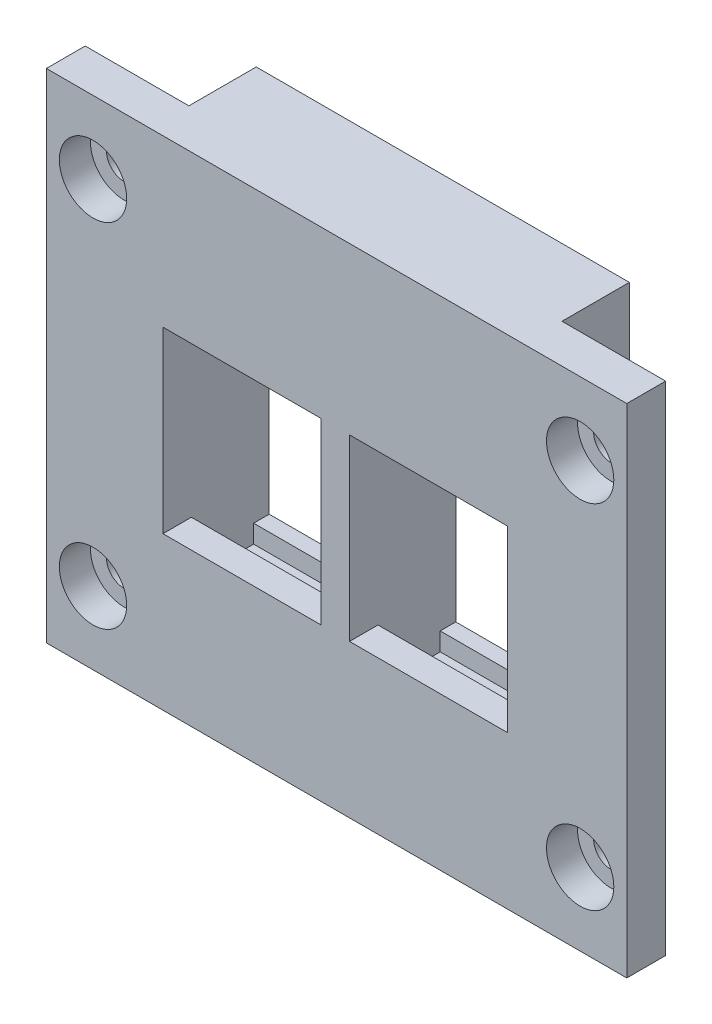
SolidWorks part; units mm, degrees
ref_plane "Front Plane" through (0, 0, 0) normal (0, 0, 1) x (1, 0, 0)
ref_plane "Top Plane" through (0, 0, 0) normal (0, 1, 0) x (1, 0, 0)
ref_plane "Right Plane" through (0, 0, 0) normal (1, 0, 0) x (0, 0, -1)
sketch "Sketch1" plane through (0, 0, 0) normal (0, 0, 1) x (1, 0, 0)
  line L1 (-18, 24) -> (18, 24)
  line L2 (-18, 24) -> (-18, -24)
  line L3 (-18, -24) -> (18, -24)
  line L4 (18, 24) -> (18, -24)
  line L5 (-18, 24) -> (18, -24) construction
  line L6 (-18, -24) -> (18, 24) construction
  point P0 (0, 0)
  dimension "D1" = 36
  dimension "D2" = 48
extrude "Boss-Extrude1" add sketch "Sketch1" along normal blind 6.5 and the other way blind 3.75
sketch "Sketch2" plane through (0, 0, 6.5) normal (0, 0, -1) x (-1, 0, 0)
  line L0 (18, -24) -> (-18, -24) construction
  line L1 (-28, -24) -> (28, -24)
  line L2 (-28, -24) -> (-28, 24)
  line L3 (-28, 24) -> (28, 24)
  line L4 (28, -24) -> (28, 24)
  line L5 (-18, 24) -> (18, 24) construction
  point P6 (0, 24)
  dimension "D1" = 56
extrude "Boss-Extrude2" add sketch "Sketch2" along normal blind 3.75
sketch "Sketch6" plane through (0, 0, 6.5) normal (0, 0, 1) x (1, 0, 0)
  line L0 (-28, -24) -> (-28, 24) construction
  line L1 (28, -24) -> (-28, -24) construction
  line L2 (-28, 24) -> (28, 24) construction
  line L3 (28, 24) -> (28, -24) construction
  point P0 (-23.5, 17)
  point P2 (-23.5, -17)
  point P4 (23.5, 17)
  point P6 (23.5, -17)
  dimension "D1" = 4.5
  dimension "D2" = 7
  dimension "D3" = 7
  dimension "D4" = 4.5
hole_wizard "CBORE for M3 SHCS1" positions "Sketch6" profile "Sketch5" counterbore size "M3" standard "ANSI Metric"
sketch "Sketch5" plane through (-23.5, 17, 6.5) normal (1, 0, 0) x (0, -1, 0)
  line L0 (0, 0) -> (0, 11.1215)
  line L1 (0, 11.1215) -> (1.7, 10.1)
  line L2 (1.7, 10.1) -> (1.7, 3)
  line L3 (1.7, 3) -> (3.25, 3)
  line L4 (3.25, 3) -> (3.25, 0)
  line L5 (3.25, 0) -> (0, 0)
  line L10 (0, 11.1215) -> (-1.7, 10.1) construction
  line L11 (0, -6.35) -> (0, 107.95) construction
  dimension "Hole Dia." = 3.4
  dimension "Hole Depth" = 10.1
  dimension "C'Bore Dia." = 6.5
  dimension "C'Bore Depth" = 3
  dimension "Drill Angle" = 118
ref_plane "Plane1" through (16.5, 0, 0) normal (1, 0, 0) x (0, 0, -1)
sketch "Sketch7" plane through (16.5, 0, 0) normal (1, 0, 0) x (0, 0, -1)
  line L0 (-5.7534, 23.5034) -> (-5.7534, 7.5034) construction
  line L1 (-5.7534, 7.5034) -> (0.7466, 7.5034) construction
  line L2 (2.2466, 7.5034) -> (2.2466, 9.0034) construction
  line L3 (4.2466, -12.9966) -> (8.1247, -12.9966) construction
  line L4 (2.2466, 9.0034) -> (0.7466, 7.5034) construction
  line L5 (2.2466, 7.5034) -> (3.7466, 7.5034) construction
  line L6 (4.2466, 7.5034) -> (4.2466, 23.5034) construction
  line L7 (2.2466, -11.4966) -> (8.1247, -11.4966) construction
  line L8 (-5.7534, 23.5034) -> (4.2466, 23.5034) construction
  line L9 (-5.7534, 23.5034) -> (2.2466, 23.5034) construction
  line L10 (-5.7534, 7.5034) -> (2.2466, 7.5034) construction
  line L11 (-0.7534, -12.9966) -> (2.2466, -11.4966) construction
  line L12 (-0.7534, -12.9966) -> (2.2466, -13.9966) construction
  line L13 (2.2466, -14.4966) -> (2.2466, -12.7466) construction
  line L14 (-0.7534, -11.4966) -> (-8.75, -11.4966) construction
  line L15 (-0.7534, -12.9966) -> (-8.75, -12.9966) construction
  line L16 (8.1247, -11.4966) -> (8.1247, -12.9966) construction
  line L19 (-6.5034, 8.0068) -> (-3.7568, 8.0068) construction
  line L22 (2.2466, 7.5034) -> (2.2466, 9.0034) construction
  line L23 (2.2466, 9.0034) -> (-3.7568, 9.0034) construction
  line L27 (-3.7568, 11.0034) -> (-3.7568, 16.0034) construction
  line L33 (-5.7534, 15.5034) -> (4.2466, 15.3434) construction
  line L47 (2.2466, -14.4966) -> (-3.7568, -14.4966) construction
  line L51 (-3.7568, -16.4966) -> (3.7466, -16.4966) construction
  line L53 (-3.7568, -16.4966) -> (-3.7568, -21.4966) construction
  line L59 (-3.7568, 11.0034) -> (3.7466, 11.0034) construction
  line L60 (-6.5034, 16.0034) -> (-3.7568, 16.0034) construction
  line L61 (-6.5034, -21.4966) -> (-3.7568, -21.4966) construction
  line L64 (-3.7568, -9.25) -> (-3.7568, -14.4966) construction
  line L65 (-3.7568, 8.0068) -> (-3.7568, 9.0034) construction
  line L69 (3.7466, -12.7466) -> (2.2466, -12.7466) construction
  line L70 (3.7466, -16.4966) -> (3.7466, -12.7466) construction
  line L71 (3.7466, -14.4966) -> (3.7466, -12.7466) construction
  line L72 (3.7466, 7.5034) -> (3.7466, 11.0034) construction
  line L73 (3.7466, 7.5034) -> (3.7466, 9.0034) construction
  line L74 (-6.5034, -9.25) -> (-3.7568, -9.25) construction
  line L75 (-6.5034, -9.25) -> (-6.5034, -21.4966) construction
  line L76 (-6.5034, 8.0068) -> (-6.5034, 16.0034) construction
  line L77 (-6.5034, 8.0068) -> (-3.7568, 8.0068)
  line L78 (-3.7568, 8.0068) -> (-3.7568, 9.0034)
  line L79 (-3.7568, 9.0034) -> (2.2466, 9.0034)
  line L80 (2.2466, 9.0034) -> (2.2466, 7.5034)
  line L81 (2.2466, 7.5034) -> (3.7466, 7.5034)
  line L83 (3.7466, -12.7466) -> (2.2466, -12.7466)
  line L84 (2.2466, -12.7466) -> (2.2466, -14.4966)
  line L85 (2.2466, -14.4966) -> (-3.7568, -14.4966)
  line L86 (-3.7568, -14.4966) -> (-3.7568, -9.25)
  line L87 (-3.7568, -9.25) -> (-6.5034, -9.25)
  line L88 (-6.5034, -9.25) -> (-6.5034, 8.0068)
  line L89 (3.7466, 7.5034) -> (6.3555, 7.5034)
  line L90 (6.3555, 7.5034) -> (6.3555, -12.7466)
  line L91 (6.3555, -12.7466) -> (3.8711, -12.7466)
  line L92 (3.8711, -12.7466) -> (3.7466, -12.7466)
  dimension "D1" = 27.5
  dimension "D2" = 5
  dimension "D3" = 1.5
  dimension "D4" = 16
  dimension "D5" = 1.5
  dimension "D6" = 6.5
  dimension "D7" = 10
  dimension "D8" = 5
extrude "Cut-Extrude1" cut sketch "Sketch7" against normal blind 15.25
pattern_linear "LPattern1" count 2 spacing 18 along (-1, 0, 0) of "Cut-Extrude1"
